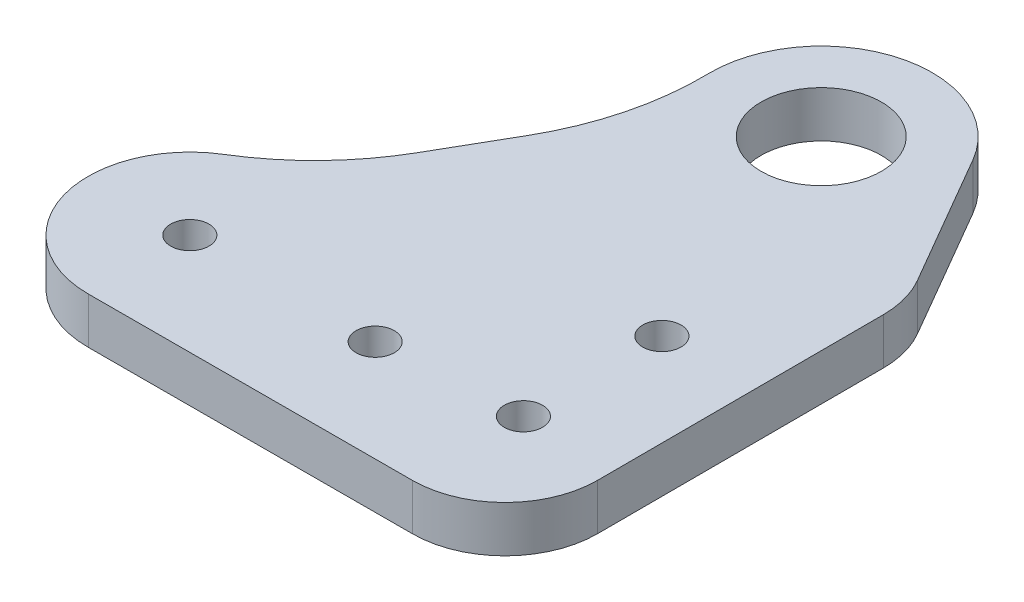
SolidWorks part; units mm, degrees
ref_plane "Front Plane" through (0, 0, 0) normal (0, 0, 1) x (1, 0, 0)
ref_plane "Top Plane" through (0, 0, 0) normal (0, 1, 0) x (1, 0, 0)
ref_plane "Right Plane" through (0, 0, 0) normal (1, 0, 0) x (0, 0, -1)
sketch "Sketch2" plane through (0, 0, 0) normal (0, 1, 0) x (1, 0, 0)
  line L0 (28.9927, -23.7473) -> (28.9312, 7.2334)
  line L1 (27.5816, 12.2308) -> (19.2852, 26.5348)
  line L2 (-7.0767, 4.7475) -> (-11.4343, -2.8348)
  line L3 (-15.9874, -33.8365) -> (19.0125, -33.7671)
  circle A0 centre (-16.0092, -22.8365) radius 2.07
  arc A1 (28.9312, 7.2334) -> (27.5816, 12.2308) centre (18.9312, 7.2136) ccw
  arc A2 (19.2852, 26.5348) -> (-3.0929, 20.2804) centre (8.9048, 20.5142) ccw
  arc A3 (-7.0767, 4.7475) -> (-3.0929, 20.2804) centre (-33.0872, 19.696) ccw
  arc A4 (-21.7602, -13.4596) -> (-11.4343, -2.8348) centre (-37.4448, 12.1137) ccw
  arc A5 (-21.7602, -13.4596) -> (-15.9874, -33.8365) centre (-16.0092, -22.8365) ccw
  arc A6 (19.0125, -33.7671) -> (28.9927, -23.7473) centre (18.9927, -23.7671) ccw
  circle A7 centre (3.9907, -22.7969) radius 2.07
  circle A8 centre (18.9887, -21.7671) radius 2.07
  circle A9 centre (18.959, -6.7671) radius 2.07
  circle A10 centre (8.9048, 20.5142) radius 6.5
  dimension "D1" = 4.14
  dimension "D2" = 13
  dimension "D3" = 10
  dimension "D4" = 12
  dimension "D5" = 30
  dimension "D6" = 11
  dimension "D7" = 3.9907
  dimension "D8" = 8.9048
  dimension "D9" = 18.9312
  dimension "D10" = 18.959
  dimension "D11" = 18.9887
  dimension "D12" = 18.9927
  dimension "D13" = 19.0125
  dimension "D14" = 19.2852
  dimension "D15" = 3.0929
  dimension "D16" = 7.0767
  dimension "D17" = 11.4343
  dimension "D18" = 4.7475
  dimension "D28" = 6.7671
  dimension "D30" = 21.7671
  dimension "D31" = 22.7969
extrude "Boss-Extrude1" add sketch "Sketch2" along normal blind 5
